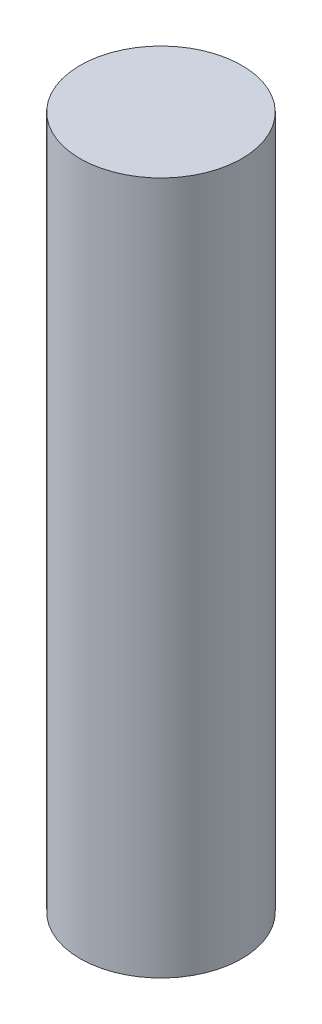
SolidWorks part; units mm, degrees
ref_plane "Front Plane" through (0, 0, 0) normal (0, 0, 1) x (1, 0, 0)
ref_plane "Top Plane" through (0, 0, 0) normal (0, 1, 0) x (1, 0, 0)
ref_plane "Right Plane" through (0, 0, 0) normal (1, 0, 0) x (0, 0, -1)
sketch "Sketch1" plane through (0, 0, 0) normal (0, 1, 0) x (1, 0, 0)
  circle A0 centre (0, 0) radius 3.5
extrude "Boss-Extrude1" add sketch "Sketch1" along normal blind 30 contours A0
